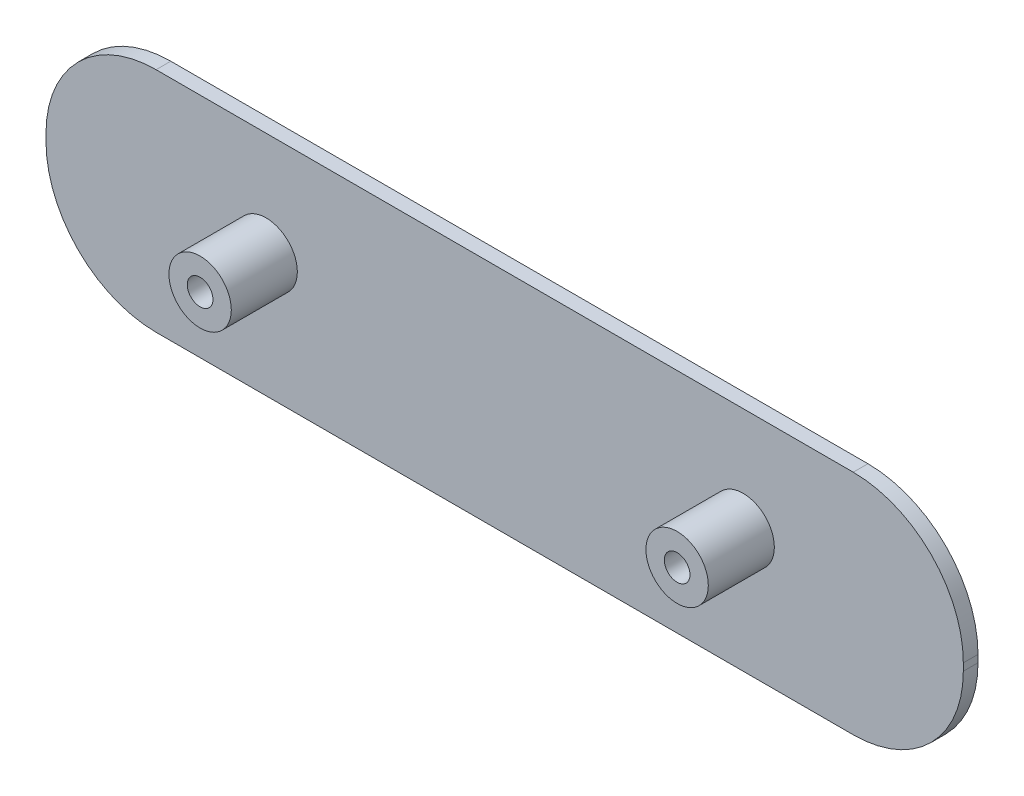
SolidWorks part; units mm, degrees
ref_plane "Plan de face" through (0, 0, 0) normal (0, 0, 1) x (1, 0, 0)
ref_plane "Plan de dessus" through (0, 0, 0) normal (0, 1, 0) x (1, 0, 0)
ref_plane "Plan de droite" through (0, 0, 0) normal (1, 0, 0) x (0, 0, -1)
sketch "Esquisse1" plane through (0, 0, 0) normal (0, 0, 1) x (1, 0, 0)
  line L1 (0, 0) -> (-125, 0)
  line L2 (0, 0) -> (0, 30.99)
  line L3 (0, 30.99) -> (-125, 30.99)
  line L4 (-125, 0) -> (-125, 30.99)
  dimension "D1" = 30.99
  dimension "D2" = 125
extrude "Boss.-Extru.1" add sketch "Esquisse1" along normal blind 2
fillet "Congé1" radius 15 4 edges at (0, 30.99, 1) (0, 0, 1) (-125, 0, 1) (-125, 30.99, 1)
sketch "Esquisse2" plane through (0, 0, 2) normal (0, 0, 1) x (1, 0, 0)
  line L0 (-110, 0) -> (-15, 0) construction
  circle A0 centre (-95, 16.75) radius 4.25
  circle A1 centre (-30, 16.75) radius 4.25
  circle A2 centre (-95, 16.75) radius 1.75
  circle A3 centre (-30, 16.75) radius 1.75
  dimension "D2" = 8.5
  dimension "D5" = 3.5
  dimension "D1" = 16.75
  dimension "D3" = 15
  dimension "D4" = 15
extrude "Boss.-Extru.2" add sketch "Esquisse2" along normal blind 9
